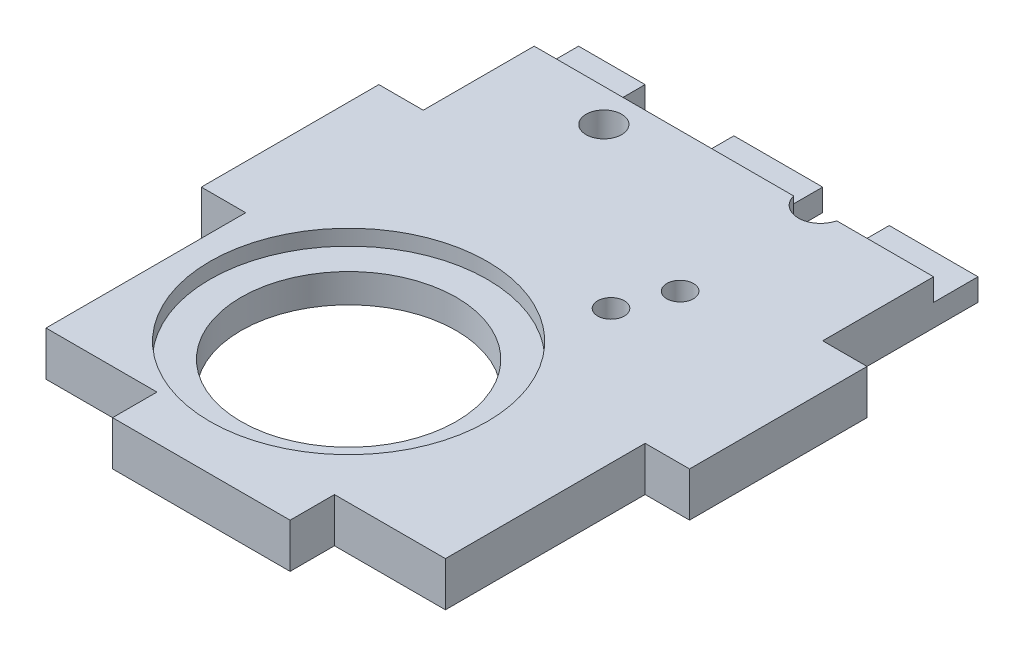
SolidWorks part; units mm, degrees
ref_plane "Front Plane" through (0, 0, 0) normal (0, 0, 1) x (1, 0, 0)
ref_plane "Top Plane" through (0, 0, 0) normal (0, 1, 0) x (1, 0, 0)
ref_plane "Right Plane" through (0, 0, 0) normal (1, 0, 0) x (0, 0, -1)
sketch "Sketch1" plane through (0, 0, 0) normal (0, 1, 0) x (1, 0, 0)
  line L1 (0, 0) -> (90, 0)
  line L2 (0, 0) -> (0, 110)
  line L3 (0, 110) -> (90, 110)
  line L4 (90, 0) -> (90, 110)
  line L5 (0, 85) -> (-10, 85)
  line L6 (0, 85) -> (0, 45)
  line L7 (0, 45) -> (-10, 45)
  line L8 (-10, 85) -> (-10, 45)
  line L9 (25, 110) -> (65, 110)
  line L13 (90, 85) -> (100, 85)
  line L14 (90, 85) -> (90, 45)
  line L15 (90, 45) -> (100, 45)
  line L16 (100, 85) -> (100, 45)
  line L17 (65, 0) -> (25, 0)
  line L18 (65, 0) -> (65, -10)
  line L19 (65, -10) -> (25, -10)
  line L20 (25, 0) -> (25, -10)
  point P23 (45, 0)
  point P24 (45, 110)
  dimension "D1" = 90
  dimension "D2" = 110
  dimension "D3" = 10
  dimension "D5" = 10
  dimension "D6" = 10
  dimension "D8" = 40
  dimension "D9" = 40
  dimension "D10" = 40
  dimension "D11" = 45
  dimension "D12" = 45
extrude "Boss-Extrude1" add sketch "Sketch1" along normal blind 10 contours L1 L4 L3 L2 | L5 L8 L7 L2 | L16 L13 L4 L15 | L1 L20 L19 L18
sketch "Sketch2" plane through (0, 10, 0) normal (0, 1, 0) x (1, 0, 0)
  line L0 (0, 102.57) -> (90.0901, 102.57) construction
  line L1 (65, 0) -> (90, 0) construction
  line L2 (23.1228, 98.57) -> (23.1228, 124.41) construction
  circle A0 centre (23.1228, 102.57) radius 4
  circle A1 centre (23.1228, 120.41) radius 4
  dimension "D2" = 8
  dimension "D4" = 8
  dimension "D1" = 102.57
  dimension "D3" = 25.84
extrude "Cut-Extrude1" cut sketch "Sketch2" against normal through all
sketch "Sketch3" plane through (0, 10, 0) normal (0, 1, 0) x (1, 0, 0)
  line L0 (80.2934, 67.48) -> (5.633, 67.48)
  line L1 (65, 0) -> (90, 0) construction
  line L2 (58.7227, 64.6909) -> (65.352, 81.4257)
  circle A0 centre (59.8276, 67.48) radius 3
  circle A1 centre (64.2471, 78.6365) radius 3
  dimension "D2" = 6
  dimension "D4" = 6
  dimension "D1" = 67.48
  dimension "D3" = 18
extrude "Cut-Extrude2" cut sketch "Sketch3" against normal through all contours L2 A1 | L2 A1 | L0 A0 L2 | L2 A0 L0 | L0 A0 L2 | L2 A0 L0
sketch "Sketch4" plane through (0, 10, 0) normal (0, 1, 0) x (1, 0, 0)
  line L0 (0, 0) -> (0, 45) construction
  line L1 (65, 0) -> (90, 0) construction
  circle A0 centre (36.72, 31.47) radius 31.25
  dimension "D3" = 62.5
  dimension "D1" = 36.72
  dimension "D2" = 31.47
extrude "Cut-Extrude3" cut sketch "Sketch4" against normal blind 3.5
sketch "Sketch5" plane through (0, 6.5, 0) normal (0, 1, 0) x (1, 0, 0)
  circle A3 centre (36.72, 31.47) radius 24.25
  circle A4 centre (36.72, 31.47) radius 24.25
  dimension "D1" = 7
extrude "Cut-Extrude4" cut sketch "Sketch5" against normal through all
sketch "Sketch6" plane through (0, 10, 0) normal (0, 1, 0) x (1, 0, 0)
  circle A0 centre (63.3149, 111.2096) radius 5
  dimension "D1" = 10
extrude "Cut-Extrude5" cut sketch "Sketch6" against normal through all
sketch "Sketch8" plane through (0, 0, -110) normal (0, 0, -1) x (-1, 0, 0)
  line L1 (-90, 0) -> (-70, 0)
  line L2 (-90, 0) -> (-90, 5)
  line L3 (-90, 5) -> (-70, 5)
  line L4 (-70, 0) -> (-70, 5)
  line L6 (0, 0) -> (-15, 0)
  line L7 (0, 0) -> (0, 5)
  line L8 (0, 5) -> (-15, 5)
  line L9 (-15, 0) -> (-15, 5)
  line L10 (-55, 0) -> (-35, 0)
  line L11 (-55, 0) -> (-55, 5)
  line L12 (-55, 5) -> (-35, 5)
  line L13 (-35, 0) -> (-35, 5)
  dimension "D1" = 20
  dimension "D2" = 15
  dimension "D3" = 20
  dimension "D4" = 15
extrude "Boss-Extrude2" add sketch "Sketch8" along normal blind 10
